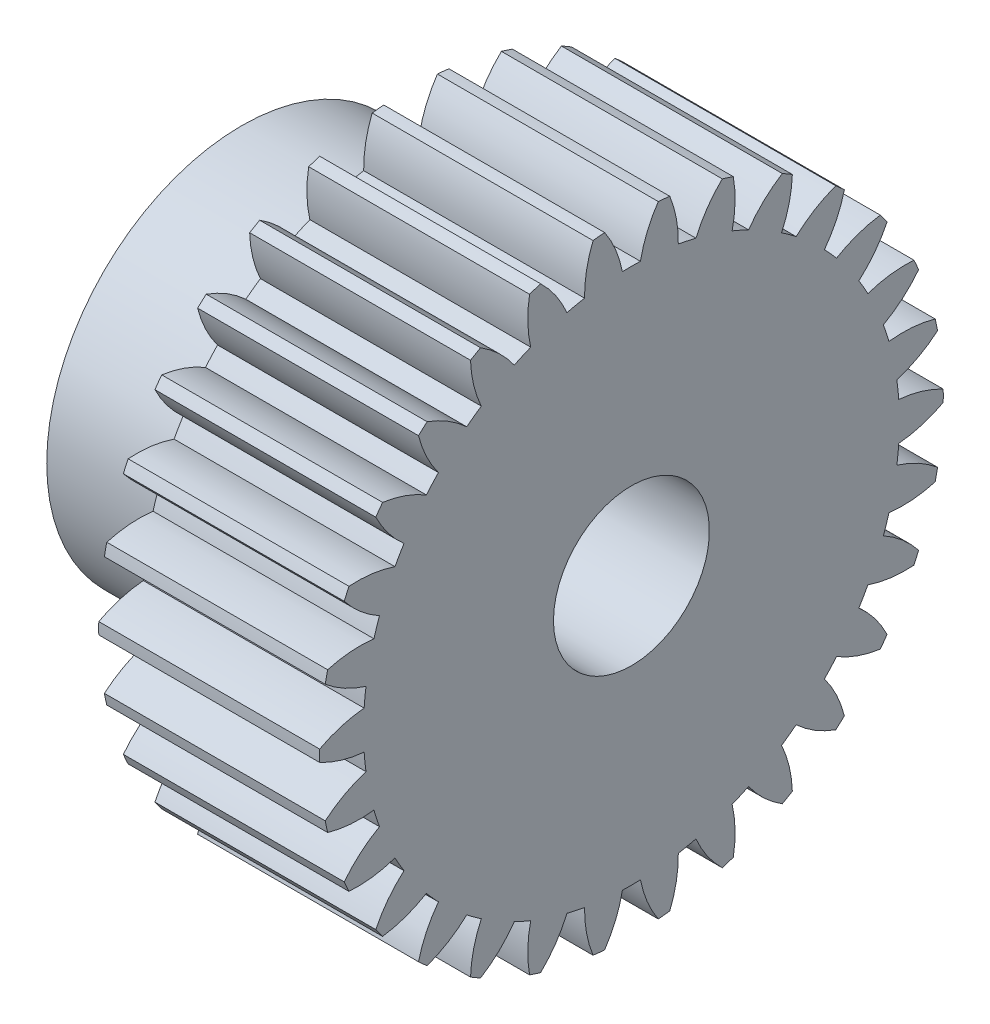
SolidWorks part; units mm, degrees
ref_plane "Plane1" through (0, 0, 0) normal (0, 0, 1) x (1, 0, 0)
ref_plane "Plane2" through (0, 0, 0) normal (0, 1, 0) x (1, 0, 0)
ref_plane "Plane3" through (0, 0, 0) normal (1, 0, 0) x (0, 0, -1)
sketch "HoldingSke" plane through (0, 0, 0) normal (0, 1, 0) x (1, 0, 0)
  line L0 (0, 0) -> (0.5774, -0.3333)
  line L1 (-15, 0) -> (100, 0) construction
  line L2 (0, 0) -> (-2.1039, 2.3779)
  line L3 (0, 0) -> (-11.863, 4.5341)
  line L4 (0, 0) -> (7.479, 4.318)
  line L5 (0, 0) -> (-28.1086, -10.4837)
  line L6 (0, 0) -> (-14.0924, -9.5082)
  line L7 (-2.1039, 2.3779) -> (4.3536, 31.6747)
  line L8 (-76.2, 54.61) -> (-73.9, 54.61)
  line L9 (-71.009, 38.7566) -> (-53.1078, 45.2721)
  line L10 (-76.2, 71.12) -> (104.1128, 71.12)
  line L11 (0, 0) -> (-17, 0)
  line L12 (-76.2, 101.6) -> (-76.147, 101.6)
  line L13 (24.9733, 27.94) -> (52.9518, 28.4284)
  line L14 (24.9733, 27.94) -> (24.9743, 27.94)
  line L15 (24.9733, 27.94) -> (100.4006, 29.5858)
  line L16 (-63.627, -1.5) -> (-12.827, -1.5)
  circle A0 centre (0, 0) radius 6
  circle A1 centre (0, 0) radius 15
  circle A2 centre (0, 0) radius 15
  circle A3 centre (0, 0) radius 6
  dimension "MHD" = 30
  dimension "Hub_dia" = 30
  dimension "Bore" = 12
  dimension "MBD" = 12
  dimension "Num_teeth" = 30
  dimension "Pitch" = 0.6667
  dimension "Overall_len" = 30
  dimension "Show_teeth" = 30
  dimension "Thickness" = 17
  dimension "OAL" = 30.0001
  dimension "T_dim" = 2.3
  dimension "Ap" = 20
  dimension "H" = 19.05
  dimension "Pitch_radius" = 180.3128
  dimension "Width" = 17
  dimension "Backlash" = 0.053
  dimension "Addendum_fac" = 1
  dimension "Dedendum_fac" = 1.25
  dimension "Clearance_fac" = 0.25
  dimension "Dedendum_add" = 0.001
  dimension "Module" = 1.5
sketch "BasProSke" plane through (0, 0, 0) normal (0, 1, 0) x (1, 0, 0)
  line L0 (-10, 0) -> (60, 0) construction
  line L1 (0, 0) -> (0, 24)
  line L2 (0, 0) -> (17, 0)
  line L3 (17, 0) -> (17, 24)
  line L4 (17, 24) -> (0, 24)
  dimension "Thickness" = 17
  dimension "Diameter" = 48
revolve "Base-Revolve" add sketch "BasProSke" angle 360 about L0
sketch "TooCutSke" plane through (0, 0, 0) normal (1, 0, 0) x (0, 0, -1)
  line L1 (0, 0) -> (0, 107) construction
  line L2 (0, 0) -> (-1.2703, 22.4641) construction
  line L3 (0, 0) -> (-4.6983, 44.7014) construction
  line L4 (-1.2703, 22.4641) -> (-2.3492, 22.3507) construction
  arc A0 (0.6933, 20.6123) -> (-0.6933, 20.6123) centre (0, 0) ccw
  arc A1 (2.0805, 23.9351) -> (-2.0805, 23.9351) centre (0, 0) ccw
  circle A2 centre (0, 0) radius 22.5 construction
  circle A3 centre (0, 0) radius 21.1431 construction
  arc A4 (-0.6933, 20.6123) -> (-2.0805, 23.9351) centre (-9.5243, 18.8764) ccw
  arc A5 (2.0805, 23.9351) -> (0.6933, 20.6123) centre (9.5243, 18.8764) ccw
  dimension "Root_dia" = 41.248
  dimension "Overcut_dia" = 48.0508
  dimension "Pitch_dia" = 45
  dimension "Base_dia" = 42.2862
  dimension "Flank_rad" = 9
  dimension "Half_ang" = 6
  dimension "Half_CT" = 1.0848
extrude "ToothCut" cut sketch "TooCutSke" along normal through all
fillet "Breaks" [suppressed] radius 0.03
fillet "RootFillets" [suppressed] radius 0.376
pattern_circular "TeethCuts" count 30 every 12 about axis through (-10, 0, 0) along (1, 0, 0) of "ToothCut", "RootFillets", "Breaks"
sketch "HubNeaOneSke" plane through (0, 0, 0) normal (-1, 0, 0) x (0, 0, 1)
  circle A0 centre (0, 0) radius 15
  dimension "Diameter" = 30
extrude "HubNearOne" add sketch "HubNeaOneSke" along normal blind 13.0001
sketch "HubNeaBotSke" plane through (0, 0, 0) normal (-1, 0, 0) x (0, 0, 1)
  circle A0 centre (0, 0) radius 15
  dimension "Diameter" = 30
extrude "HubNearBoth" [suppressed] add sketch "HubNeaBotSke" along normal blind 6.5
ref_plane "FarPln" through (17, 0, 0) normal (1, 0, 0) x (0, 0, -1)
sketch "HubFarSke" plane through (17, 0, 0) normal (1, 0, 0) x (0, 0, -1)
  circle A0 centre (0, 0) radius 15
  dimension "Diameter" = 30
extrude "HubFar" [suppressed] add sketch "HubFarSke" along normal blind 6.5
sketch "BorSke" plane through (0, 0, 0) normal (1, 0, 0) x (0, 0, -1)
  circle A0 centre (0, 0) radius 6
  dimension "Diameter" = 12
extrude "Bore" cut sketch "BorSke" along normal mid plane 60.0001
sketch "KeySke" plane through (0, 0, 0) normal (1, 0, 0) x (0, 0, -1)
  line L0 (-2.5, 0) -> (-2.5, 8.3)
  line L1 (-2.5, 8.3) -> (2.5, 8.3)
  line L2 (2.5, 8.3) -> (2.5, 0)
  line L3 (0, 0) -> (0, 34) construction
  line L4 (-2.5, 0) -> (2.5, 0)
  dimension "Offset" = 8.3
  dimension "Width" = 5
extrude "Keyway" [suppressed] cut sketch "KeySke" along normal mid plane 60.0001
pattern_circular "Keyway2" [suppressed] count 2 every 90 about axis through (-10, 0, 0) along (1, 0, 0)
equation "' \"Module@HoldingSke\" = 6.35"
equation "' \"Num_teeth@HoldingSke\" = 12"
equation "' \"Ap@HoldingSke\" =  20"
equation "' \"Ap@HoldingSke\" = 20"
equation "' \"Width@HoldingSke\" = 0.5 * 25.4"
equation "' \"Hub_dia@HoldingSke\"= 1 * 25.4"
equation "' \"Hub_dia@HoldingSke\" = 1 * 25.4"
equation "' \"Overall_len@HoldingSke\" = 1.0 * 25.4"
equation "' \"Bore@HoldingSke\" = 0.75 * 25.4"
equation "' \"T_dim@HoldingSke\" = 0.1 * 25.4"
equation "' \"Width@KeySke\" = 0.25 * 25.4"
equation "' \"Show_teeth@HoldingSke\" = 13"
equation "' \"Backlash@HoldingSke\" = 0.009 * 25.4"
equation "' \"Addendum_fac@HoldingSke\" = 1.0"
equation "' \"Dedendum_fac@HoldingSke\" = 1.25"
equation "' \"Dedendum_add@HoldingSke\" = 0.00005 * 25.4"
equation "' \"Clearance_fac@HoldingSke\" = 0.25"
equation "\"Pitch@HoldingSke\" = 1 / \"Module@HoldingSke\""
equation "\"Overcut_dia@TooCutSke\" = (\"Num_teeth@HoldingSke\" + 2 * \"Addendum_fac@HoldingSke\") / \"Pitch@HoldingSke\" + 0.002 * 25.4"
equation "\"Pitch_dia@TooCutSke\" = \"Num_teeth@HoldingSke\" / \"Pitch@HoldingSke\""
equation "\"Base_dia@TooCutSke\" = \"Num_teeth@HoldingSke\" / \"Pitch@HoldingSke\" * cos((\"Ap@HoldingSke\"  * 3.14159265 / 180))"
equation "\"Root_dia@TooCutSke\" = (\"Num_teeth@HoldingSke\" + 2) / \"Pitch@HoldingSke\" - 2 * (\"Addendum_fac@HoldingSke\" + \"Dedendum_fac@HoldingSke\") / \"Pitch@HoldingSke\" - \"Dedendum_add@HoldingSke\" * 2"
equation "\"Half_ang@TooCutSke\" = 180 / \"Num_teeth@HoldingSke\""
equation "\"Half_CT@TooCutSke\" = \"Num_teeth@HoldingSke\" / \"Pitch@HoldingSke\" * sin((3.14159265 / 2 / \"Num_teeth@HoldingSke\")) / 2 - 7 * \"Backlash@HoldingSke\" / 4"
equation "\"Flank_rad@TooCutSke\" = \"Num_teeth@HoldingSke\" / \"Pitch@HoldingSke\" / 5"
equation "\"Radius@RootFillets\" = \"Clearance_fac@HoldingSke\" / \"Pitch@HoldingSke\" + \"Dedendum_add@HoldingSke\""
equation "\"Break_rad@Breaks\" = 0.02 / \"Pitch@HoldingSke\""
equation "\"Thickness@HoldingSke\" = \"Width@HoldingSke\""
equation "\"OAL@HoldingSke\" = \"Thickness@HoldingSke\""
equation "\"MHD@HoldingSke\" = (\"Num_teeth@HoldingSke\" + 2) / \"Pitch@HoldingSke\" - 2 * (\"Addendum_fac@HoldingSke\" + \"Dedendum_fac@HoldingSke\")  / \"Pitch@HoldingSke\" - \"Dedendum_add@HoldingSke\" * 2"
equation "\"MBD@HoldingSke\" = (\"Num_teeth@HoldingSke\" + 2) / \"Pitch@HoldingSke\" - 2 * (\"Addendum_fac@HoldingSke\" + \"Dedendum_fac@HoldingSke\")  / \"Pitch@HoldingSke\" - \"Dedendum_add@HoldingSke\" * 2 - 0.002 * 25.4"
equation "\"MHD@HoldingSke\" = ((sgn( \"MHD@HoldingSke\" - \"Hub_dia@HoldingSke\" )-1)*( \"MHD@HoldingSke\" - \"Hub_dia@HoldingSke\" ))/-2+ \"Hub_dia@HoldingSke\""
equation "\"MBD@HoldingSke\" = ((sgn( \"MBD@HoldingSke\" - \"Bore@HoldingSke\" )-1)*( \"MBD@HoldingSke\" - \"Bore@HoldingSke\" ))/-2+ \"Bore@HoldingSke\""
equation "\"OAL@HoldingSke\" = ((sgn( \"OAL@HoldingSke\" - \"Overall_len@HoldingSke\" )+1)*( \"OAL@HoldingSke\" - \"Overall_len@HoldingSke\" ))/2 + \"Overall_len@HoldingSke\" + 0.000002 * 25.4"
equation "\"Num_teeth@TeethCuts\" = int( \"Show_teeth@HoldingSke\" ) + 1"
equation "\"Num_teeth@TeethCuts\" = ((sgn( \"Num_teeth@TeethCuts\" - \"Num_teeth@HoldingSke\" )-1)*( \"Num_teeth@TeethCuts\" - \"Num_teeth@HoldingSke\" ))/-2+ \"Num_teeth@HoldingSke\""
equation "\"Num_teeth@TeethCuts\" = ((sgn( \"Num_teeth@TeethCuts\" - 2.0)+1)*( \"Num_teeth@TeethCuts\" - 2.0))/2 +2.0"
equation "\"Angle@TeethCuts\" = 360.0 / \"Num_teeth@HoldingSke\""
equation "\"Diameter@BasProSke\" = (\"Num_teeth@HoldingSke\" + 2 * \"Addendum_fac@HoldingSke\") / \"Pitch@HoldingSke\""
equation "\"Thickness@BasProSke\"  = \"Thickness@HoldingSke\""
equation "' \"Fillet_rad@BasProSke\" =  \"Thickness@HoldingSke\" * 0.05"
equation "' \"Fillet_rad@BasProSke\" = \"Thickness@HoldingSke\" * 0.05"
equation "\"MHD@HoldingSke\" = ((sgn( \"MHD@HoldingSke\" - \"Root_dia@TooCutSke\" )-1)*( \"MHD@HoldingSke\" - \"Root_dia@TooCutSke\" ))/-2+ \"Root_dia@TooCutSke\""
equation "\"Diameter@HubNeaOneSke\" = \"MHD@HoldingSke\""
equation "\"Length@HubNearOne\" = \"OAL@HoldingSke\" - \"Thickness@BasProSke\""
equation "\"Diameter@HubNeaBotSke\" = \"MHD@HoldingSke\""
equation "\"Length@HubNearBoth\" = ( \"OAL@HoldingSke\" - \"Thickness@BasProSke\" ) / 2.0"
equation "\"Thickness@FarPln\" = \"Thickness@BasProSke\""
equation "\"Diameter@HubFarSke\" = \"MHD@HoldingSke\""
equation "\"Length@HubFar\" = ( \"OAL@HoldingSke\" - \"Thickness@BasProSke\" ) / 2.0"
equation "\"Diameter@BorSke\" = \"MBD@HoldingSke\""
equation "\"D1@Bore\" = \"OAL@HoldingSke\" * 2.0"
equation "\"D1@Keyway\" = \"OAL@HoldingSke\" * 2.0"
equation "\"Offset@KeySke\" = \"T_dim@HoldingSke\" + \"MBD@HoldingSke\" / 2.0"
